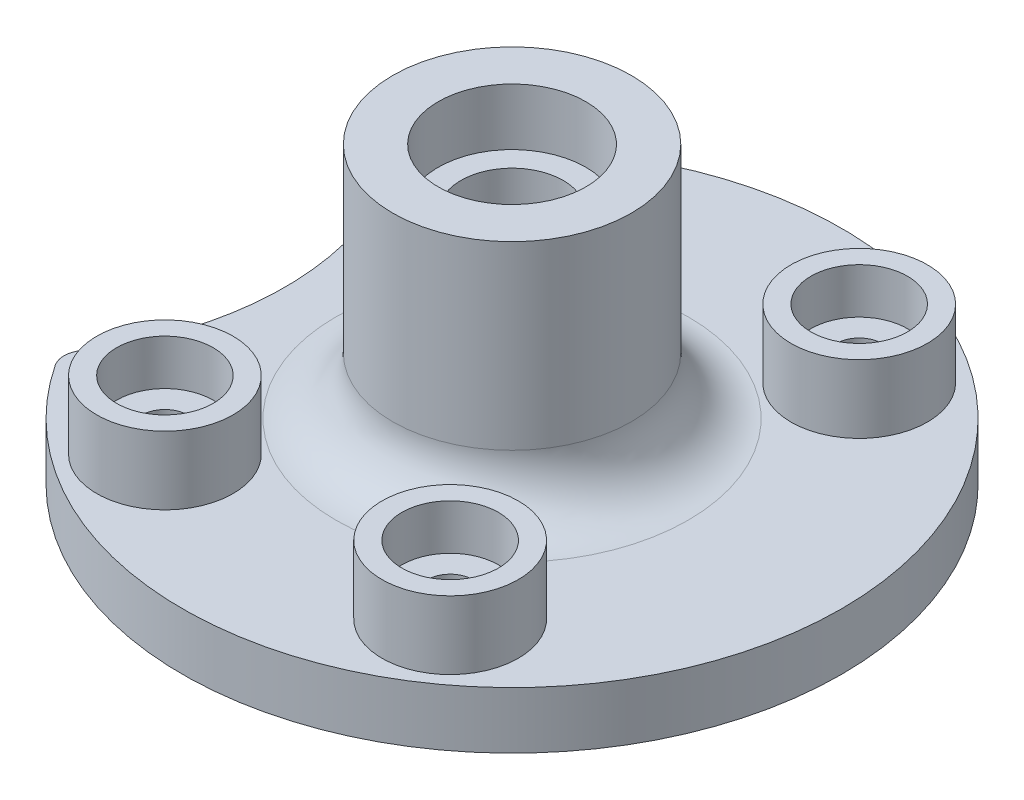
SolidWorks part; units mm, degrees
ref_plane "Plan de face" through (0, 0, 0) normal (0, 0, 1) x (1, 0, 0)
ref_plane "Plan de dessus" through (0, 0, 0) normal (0, 1, 0) x (1, 0, 0)
ref_plane "Plan de droite" through (0, 0, 0) normal (1, 0, 0) x (0, 0, -1)
sketch "Esquisse2" plane through (0, 0, 0) normal (1, 0, 0) x (0, 0, -1)
  line L2 (6.5, 5) -> (6.5, 10)
  line L3 (6.5, 10) -> (10.5, 10)
  line L4 (10.5, 10) -> (10.5, -10.9)
  line L5 (10.5, -10.9) -> (6.5, -10.9)
  line L6 (6.5, -10.9) -> (6.5, -5)
  line L9 (0, 0) -> (4.5, 0) construction
  line L11 (6.5, 5) -> (4.5, 5)
  line L12 (4.5, 5) -> (4.5, 0)
  line L14 (6.5, -5) -> (4.5, -5)
  line L15 (4.5, -5) -> (4.5, 0)
  line L16 (0, 0) -> (0, 6.6645) construction
  dimension "D2" = 5
  dimension "D3" = 5.9
  dimension "D4" = 4.5
  dimension "D5" = 6.5
  dimension "D8" = 5
  dimension "D9" = 5
  dimension "D10" = 4
revolve "Révolution1" add sketch "Esquisse2" angle 360 about L16
sketch "Esquisse3" plane through (0, -10.9, 0) normal (0, 1, 0) x (1, 0, 0)
  line L0 (0, 0) -> (-45, 0) construction
  circle A0 centre (0, 0) radius 6.5
  circle A2 centre (0, 0) radius 6.5 construction
  arc A4 (-24.9, 14.8657) -> (-24.9, -14.8657) centre (-45, 0) cw
  arc A5 (-24.9, 14.8657) -> (-24.9, -14.8657) centre (0, 0) cw
  dimension "D1" = 29
  dimension "D3" = 25
  dimension "D2" = 45
extrude "Boss.-Extru.1" add sketch "Esquisse3" against normal blind 5
fillet "Congé1" radius 5 1 edges at (0, -10.9, -10.5)
sketch "Esquisse5" plane through (0, -10.9, 0) normal (0, 1, 0) x (1, 0, 0)
  line L0 (0, 0) -> (-34, 0) construction
  line L1 (-34, 0) -> (-12.5508, 17.9981) construction
  circle A0 centre (-12.5508, 17.9981) radius 6
  circle A1 centre (-12.5508, 17.9981) radius 4.25
  circle A2 centre (-12.5508, -17.9981) radius 4.25
  circle A3 centre (-12.5508, -17.9981) radius 6
  dimension "D4" = 8.5
  dimension "D5" = 12
  dimension "D1" = 34
  dimension "D2" = 40
  dimension "D3" = 28
extrude "Boss.-Extru.3" add sketch "Esquisse5" along normal blind 6
sketch "Esquisse8" plane through (0, -10.9, 0) normal (0, 1, 0) x (1, 0, 0)
  circle A0 centre (-12.5508, -17.9981) radius 4.25
  circle A1 centre (-12.5508, -17.9981) radius 4.25 construction
  circle A2 centre (-12.5508, 17.9981) radius 4.25
  circle A3 centre (-12.5508, 17.9981) radius 4.25 construction
extrude "Boss.-Extru.4" add sketch "Esquisse8" along normal blind 2
sketch "Esquisse6" plane through (0, -10.9, 0) normal (0, 1, 0) x (1, 0, 0)
  circle A0 centre (-12.5508, -17.9981) radius 2
  circle A1 centre (-12.5508, 17.9981) radius 2
  dimension "D1" = 4
  dimension "D2" = 4
extrude "Enlèv. mat.-Extru.1" cut sketch "Esquisse6" against normal through all both and the other way through all
sketch "Esquisse7" plane through (0, -15.9, 0) normal (0, -1, 0) x (1, 0, 0)
  circle A0 centre (-12.5508, 17.9981) radius 3
  circle A1 centre (-12.5508, -17.9981) radius 3
  dimension "D1" = 6
  dimension "D2" = 6
extrude "Enlèv. mat.-Extru.2" cut sketch "Esquisse7" against normal blind 3
fillet "Congé2" radius 2 2 edges at (-24.9, -13.4, -14.8657) (-24.9, -13.4, 14.8657)
mirror "Symétrie1" about plane through (0, 0, 0) normal (1, 0, 0) of "Enlèv. mat.-Extru.2", "Enlèv. mat.-Extru.1", "Boss.-Extru.4", "Boss.-Extru.3"
